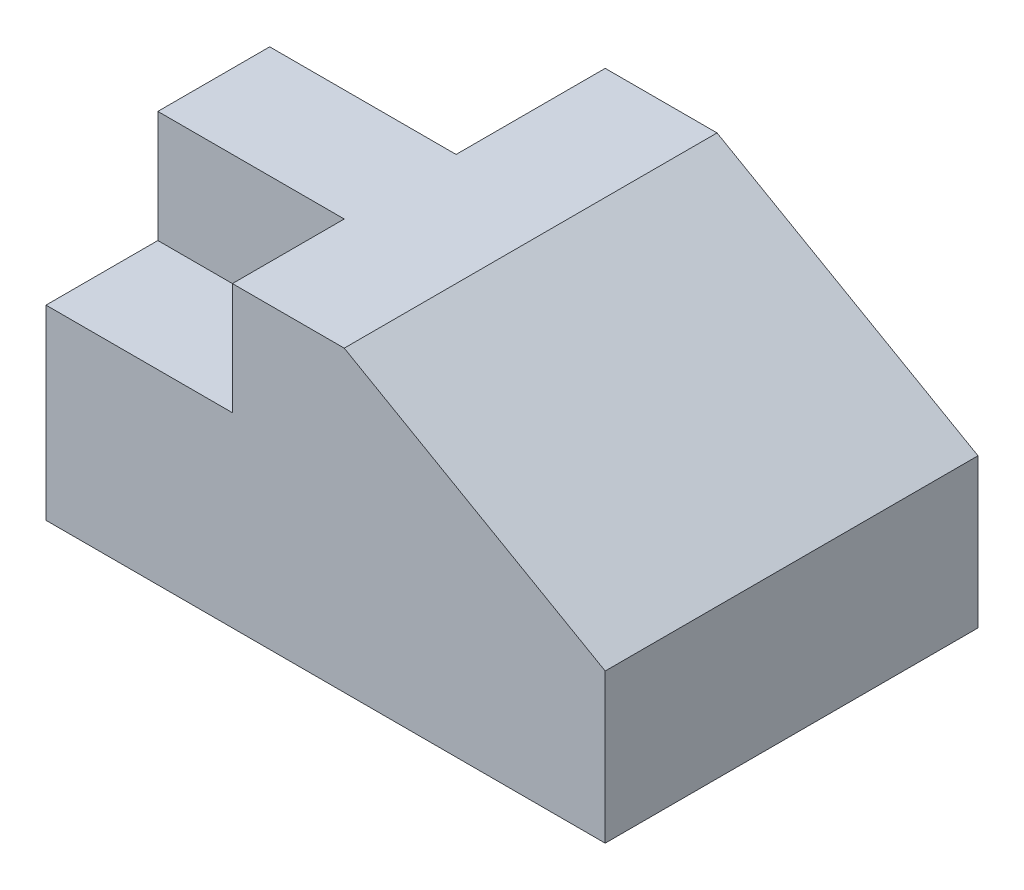
SolidWorks part; units mm, degrees
ref_plane "Front Plane" through (0, 0, 0) normal (0, 0, 1) x (1, 0, 0)
ref_plane "Top Plane" through (0, 0, 0) normal (0, 1, 0) x (1, 0, 0)
ref_plane "Right Plane" through (0, 0, 0) normal (1, 0, 0) x (0, 0, -1)
sketch "Sketch1" plane through (0, 0, 0) normal (0, 0, 1) x (1, 0, 0)
  line L0 (0, 0) -> (0, 50)
  line L1 (0, 50) -> (50, 50)
  line L2 (50, 50) -> (50, 80)
  line L3 (50, 80) -> (80, 80)
  line L4 (80, 80) -> (150, 40)
  line L5 (150, 40) -> (150, 0)
  line L6 (150, 0) -> (0, 0)
  dimension "D1" = 50
  dimension "D2" = 50
  dimension "D3" = 30
  dimension "D4" = 30
  dimension "D5" = 150
  dimension "D6" = 40
extrude "Boss-Extrude1" add sketch "Sketch1" along normal blind 100
sketch "Sketch2" plane through (0, 80, 0) normal (0, 1, 0) x (1, 0, 0)
  line L0 (0, -100) -> (0, 0) construction
  line L1 (0, -40) -> (50, -40)
  line L2 (0, -40) -> (0, -70)
  line L3 (0, -70) -> (50, -70)
  line L4 (50, -40) -> (50, -70)
  line L5 (50, -100) -> (50, 0) construction
  line L6 (50, 0) -> (0, 0) construction
  line L7 (50, -100) -> (0, -100) construction
  line L11 (30, -40) -> (50, -40)
  dimension "D1" = 40
  dimension "D2" = 30
extrude "Boss-Extrude2" add sketch "Sketch2" against normal blind 30 contours L1 L2 L3 L4
sketch "Sketch4" plane through (0, 50, 0) normal (0, 1, 0) x (1, 0, 0)
  line L1 (0, 0) -> (50, 0)
  line L2 (0, 0) -> (0, -40)
  line L3 (0, -40) -> (50, -40)
  line L4 (50, 0) -> (50, -40)
extrude "Cut-Extrude2" cut sketch "Sketch4" against normal through all
